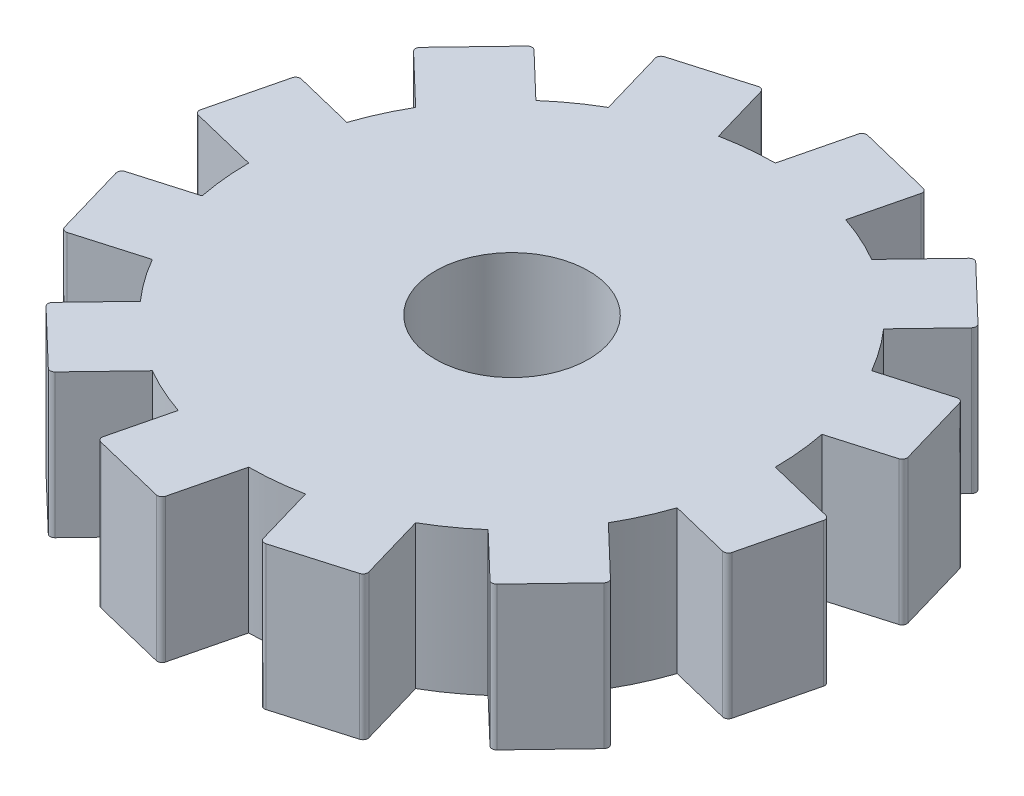
SolidWorks part; units mm, degrees
material "ABS PC"
ref_plane "Front Plane" through (0, 0, 0) normal (0, 0, 1) x (1, 0, 0)
ref_plane "Top Plane" through (0, 0, 0) normal (0, 1, 0) x (1, 0, 0)
ref_plane "Right Plane" through (0, 0, 0) normal (1, 0, 0) x (0, 0, -1)
sketch "Sketch1" plane through (0, 0, 0) normal (0, 1, 0) x (1, 0, 0)
  circle A0 centre (0, 0) radius 7
  dimension "D1" = 14
extrude "Boss-Extrude1" add sketch "Sketch1" along normal blind 3 contours A0
sketch "Sketch2" plane through (0, 3, 0) normal (0, 1, 0) x (1, 0, 0)
  line L0 (0, 13.4205) -> (0, -11.8066) construction
  line L1 (0, 5.5) -> (0.3416, 6.8933)
  line L2 (0.4626, 6.9666) -> (1.9967, 6.5905)
  line L3 (2.07, 6.4695) -> (1.7612, 5.2104)
  line L4 (2.75, 4.7631) -> (3.7425, 5.799)
  line L5 (3.8839, 5.802) -> (5.0244, 4.7092)
  line L6 (5.0274, 4.5678) -> (4.1304, 3.6317)
  line L7 (4.7631, 2.75) -> (6.1406, 3.1508)
  line L8 (6.2646, 3.0827) -> (6.7059, 1.5661)
  line L9 (6.6378, 1.4421) -> (5.3929, 1.0799)
  line L10 (5.5, 0) -> (6.8933, -0.3416)
  line L11 (6.9666, -0.4626) -> (6.5905, -1.9967)
  line L12 (6.4695, -2.07) -> (5.2104, -1.7612)
  line L13 (4.7631, -2.75) -> (5.799, -3.7425)
  line L14 (5.802, -3.8839) -> (4.7092, -5.0244)
  line L15 (4.5678, -5.0274) -> (3.6317, -4.1304)
  line L16 (2.75, -4.7631) -> (3.1508, -6.1406)
  line L17 (3.0827, -6.2646) -> (1.5661, -6.7059)
  line L18 (1.4421, -6.6378) -> (1.0799, -5.3929)
  line L19 (0, -5.5) -> (-0.3416, -6.8933)
  line L20 (-0.4626, -6.9666) -> (-1.9967, -6.5905)
  line L21 (-2.07, -6.4695) -> (-1.7612, -5.2104)
  line L22 (-2.75, -4.7631) -> (-3.7425, -5.799)
  line L23 (-3.8839, -5.802) -> (-5.0244, -4.7092)
  line L24 (-5.0274, -4.5678) -> (-4.1304, -3.6317)
  line L25 (-4.7631, -2.75) -> (-6.1406, -3.1508)
  line L26 (-6.2646, -3.0827) -> (-6.7059, -1.5661)
  line L27 (-6.6378, -1.4421) -> (-5.3929, -1.0799)
  line L28 (-5.5, 0) -> (-6.8933, 0.3416)
  line L29 (-6.9666, 0.4626) -> (-6.5905, 1.9967)
  line L30 (-6.4695, 2.07) -> (-5.2104, 1.7612)
  line L31 (-4.7631, 2.75) -> (-5.799, 3.7425)
  line L32 (-5.802, 3.8839) -> (-4.7092, 5.0244)
  line L33 (-4.5678, 5.0274) -> (-3.6317, 4.1304)
  line L34 (-2.75, 4.7631) -> (-3.1508, 6.1406)
  line L35 (-3.0827, 6.2646) -> (-1.5661, 6.7059)
  line L36 (-1.4421, 6.6378) -> (-1.0799, 5.3929)
  circle A0 centre (0, 0) radius 5.5
  circle A1 centre (0, 0) radius 7
  circle A2 centre (0, 0) radius 7
  arc A3 (0, 5.5) -> (1.7612, 5.2104) centre (0, 0) cw
  arc A4 (2.07, 6.4695) -> (1.9967, 6.5905) centre (1.9728, 6.4934) ccw
  arc A5 (0.4626, 6.9666) -> (0.3416, 6.8933) centre (0.4388, 6.8695) ccw
  circle A6 centre (0, 0) radius 7 construction
  arc A7 (3.8839, 5.802) -> (3.7425, 5.799) centre (3.8147, 5.7298) ccw
  circle A8 centre (0, 0) radius 7
  arc A9 (5.0274, 4.5678) -> (5.0244, 4.7092) centre (4.9552, 4.637) ccw
  circle A10 centre (0, 0) radius 5.5
  arc A11 (6.2646, 3.0827) -> (6.1406, 3.1508) centre (6.1686, 3.0548) ccw
  circle A12 centre (0, 0) radius 7
  arc A13 (6.6378, 1.4421) -> (6.7059, 1.5661) centre (6.6098, 1.5382) ccw
  circle A14 centre (0, 0) radius 5.5
  arc A15 (6.9666, -0.4626) -> (6.8933, -0.3416) centre (6.8695, -0.4388) ccw
  circle A16 centre (0, 0) radius 7
  arc A17 (6.4695, -2.07) -> (6.5905, -1.9967) centre (6.4934, -1.9728) ccw
  circle A18 centre (0, 0) radius 5.5
  arc A19 (5.802, -3.8839) -> (5.799, -3.7425) centre (5.7298, -3.8147) ccw
  circle A20 centre (0, 0) radius 7
  arc A21 (4.5678, -5.0274) -> (4.7092, -5.0244) centre (4.637, -4.9552) ccw
  circle A22 centre (0, 0) radius 5.5
  arc A23 (3.0827, -6.2646) -> (3.1508, -6.1406) centre (3.0548, -6.1686) ccw
  circle A24 centre (0, 0) radius 7
  arc A25 (1.4421, -6.6378) -> (1.5661, -6.7059) centre (1.5382, -6.6098) ccw
  circle A26 centre (0, 0) radius 5.5
  arc A27 (-0.4626, -6.9666) -> (-0.3416, -6.8933) centre (-0.4388, -6.8695) ccw
  circle A28 centre (0, 0) radius 7
  arc A29 (-2.07, -6.4695) -> (-1.9967, -6.5905) centre (-1.9728, -6.4934) ccw
  circle A30 centre (0, 0) radius 5.5
  arc A31 (-3.8839, -5.802) -> (-3.7425, -5.799) centre (-3.8147, -5.7298) ccw
  circle A32 centre (0, 0) radius 7
  arc A33 (-5.0274, -4.5678) -> (-5.0244, -4.7092) centre (-4.9552, -4.637) ccw
  circle A34 centre (0, 0) radius 5.5
  arc A35 (-6.2646, -3.0827) -> (-6.1406, -3.1508) centre (-6.1686, -3.0548) ccw
  circle A36 centre (0, 0) radius 7
  arc A37 (-6.6378, -1.4421) -> (-6.7059, -1.5661) centre (-6.6098, -1.5382) ccw
  circle A38 centre (0, 0) radius 5.5
  arc A39 (-6.9666, 0.4626) -> (-6.8933, 0.3416) centre (-6.8695, 0.4388) ccw
  circle A40 centre (0, 0) radius 7
  arc A41 (-6.4695, 2.07) -> (-6.5905, 1.9967) centre (-6.4934, 1.9728) ccw
  circle A42 centre (0, 0) radius 5.5
  arc A43 (-5.802, 3.8839) -> (-5.799, 3.7425) centre (-5.7298, 3.8147) ccw
  circle A44 centre (0, 0) radius 7
  arc A45 (-4.5678, 5.0274) -> (-4.7092, 5.0244) centre (-4.637, 4.9552) ccw
  circle A46 centre (0, 0) radius 5.5
  arc A47 (-3.0827, 6.2646) -> (-3.1508, 6.1406) centre (-3.0548, 6.1686) ccw
  circle A48 centre (0, 0) radius 7
  arc A49 (-1.4421, 6.6378) -> (-1.5661, 6.7059) centre (-1.5382, 6.6098) ccw
  circle A50 centre (0, 0) radius 5.5
  point P17 (0.3655, 6.9905)
  point P131 (0, 0)
  circle M7 centre (0, 0) radius 7
  dimension "D2" = 11
  dimension "D4" = 0.1
  dimension "D3" = 90
  dimension "D1" = 0
  dimension "D5" = 12
extrude "Cut-Extrude1" cut sketch "Sketch2" against normal blind 3 and the other way through all contours L0 A48 L19 A27 L20 A29 L21 A0 L22 A31 L23 A33 L24 L25 A35 L26 A37 L27 L28 A39 L29 A41 L30 L31 A43 L32 A45 L33 L34 A47 L35 A49 L36 | L0 L1 A5 L2 A4 L3 A0 L4 A7 L5 A9 L6 L7 A11 L8 A13 L9 L10 A15 L11 A17 L12 L13 A19 L14 A21 L15 L16 A23 L17 A25 L18 M7
sketch "Sketch5" plane through (0, 3, 0) normal (0, 1, 0) x (1, 0, 0)
  circle A0 centre (0, 0) radius 1.6
  dimension "D1" = 3.2
extrude "Cut-Extrude2" cut sketch "Sketch5" against normal blind 3
